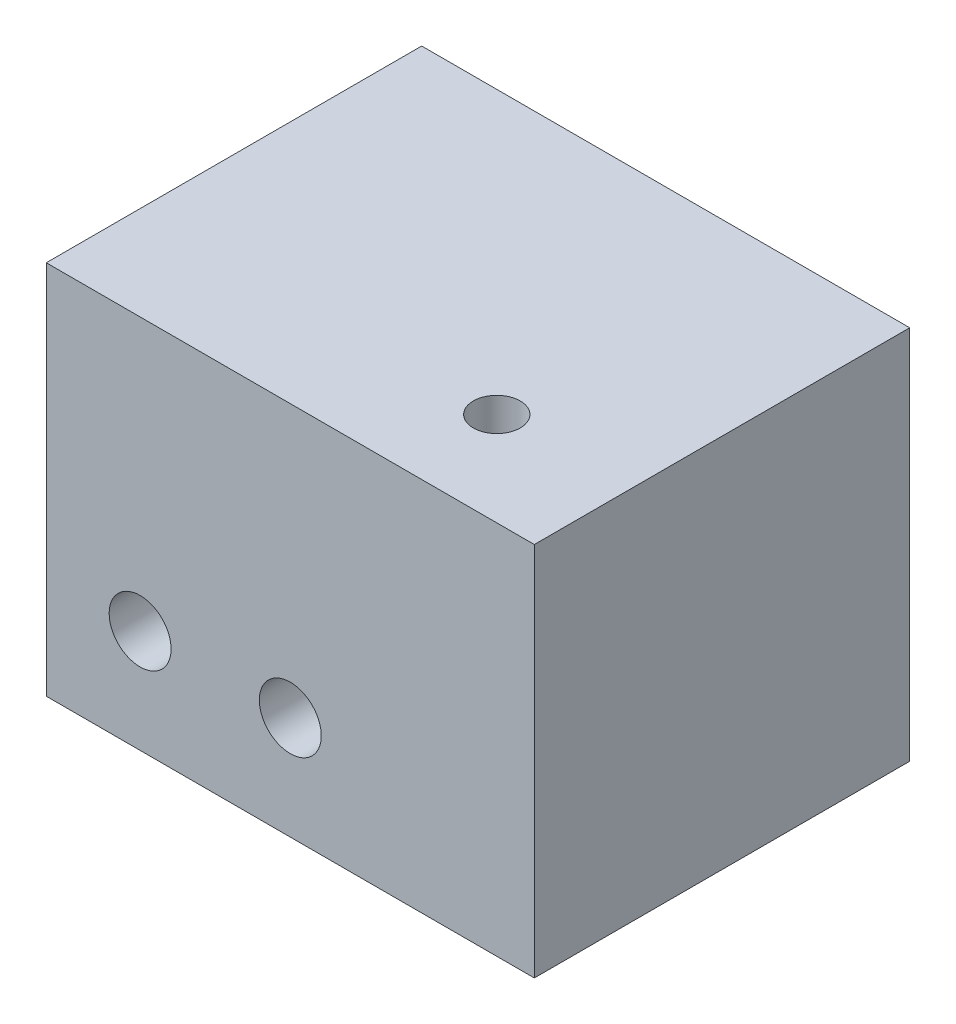
SolidWorks part; units mm, degrees
ref_plane "前视基准面" through (0, 0, 0) normal (0, 0, 1) x (1, 0, 0)
ref_plane "上视基准面" through (0, 0, 0) normal (0, 1, 0) x (1, 0, 0)
ref_plane "右视基准面" through (0, 0, 0) normal (1, 0, 0) x (0, 0, -1)
other "Configuration Table"
sketch "草图1" plane through (0, 0, 0) normal (0, 1, 0) x (1, 0, 0)
  line L1 (-13, -10) -> (13, -10)
  line L2 (-13, -10) -> (-13, 10)
  line L3 (-13, 10) -> (13, 10)
  line L4 (13, -10) -> (13, 10)
  line L5 (0, 10) -> (0, -10) construction
  line L6 (-13, 0) -> (13, 0) construction
  point P0 (0, 0)
  dimension "D1" = 26
  dimension "D2" = 20
extrude "凸台-拉伸1" add sketch "草图1" along normal blind 25
sketch "草图2" plane through (0, 0, 0) normal (0, -1, 0) x (1, 0, 0)
  line L1 (-13, 10) -> (13, 10) construction
  line L2 (13, -10) -> (-13, -10) construction
  line L4 (5, 2.0657) -> (5, -10)
  line L5 (5, -10) -> (7, -10)
  line L6 (7, 2.0657) -> (7, -10)
  line L7 (5, 2.0657) -> (7, 2.0657) construction
  line L8 (13, 10) -> (13, -10) construction
  arc A0 (7, 2.0657) -> (5, 2.0657) centre (6, 5) ccw
  dimension "D1" = 6.2
  dimension "D2" = 7
  dimension "D3" = 5
  dimension "D4" = 2
extrude "切除-拉伸1" cut sketch "草图2" against normal blind 16
fillet "圆角1" radius 2 2 edges at (7, 8, 2.0657) (5, 8, 2.0657)
sketch "草图3" plane through (0, 16, 0) normal (0, -1, 0) x (1, 0, 0)
  circle A0 centre (6, 5) radius 1.25
  dimension "D1" = 2.5
extrude "切除-拉伸2" cut sketch "草图3" against normal through all
sketch "草图4" plane through (0, 0, -10) normal (0, 0, -1) x (-1, 0, 0)
  line L0 (13, 25) -> (13, 0) construction
  line L2 (-13, 25) -> (13, 25) construction
  circle A0 centre (8, 10.5) radius 1.65
  circle A1 centre (0, 10.5) radius 1.65
  point P8 (0, 0)
  dimension "D1" = 3.3
  dimension "D2" = 5
  dimension "D3" = 14.5
  dimension "D4" = 8
extrude "切除-拉伸3" cut sketch "草图4" against normal through all
sketch "草图5" plane through (13, 0, 0) normal (1, 0, 0) x (0, 0, -1)
  line L0 (10, 25) -> (10, 0) construction
  line L1 (-10, 0) -> (10, 0)
  line L2 (-10, 0) -> (-10, 5)
  line L3 (-10, 5) -> (10, 5)
  line L4 (10, 0) -> (10, 5)
  dimension "D1" = 5
extrude "切除-拉伸4" cut sketch "草图5" against normal through all
